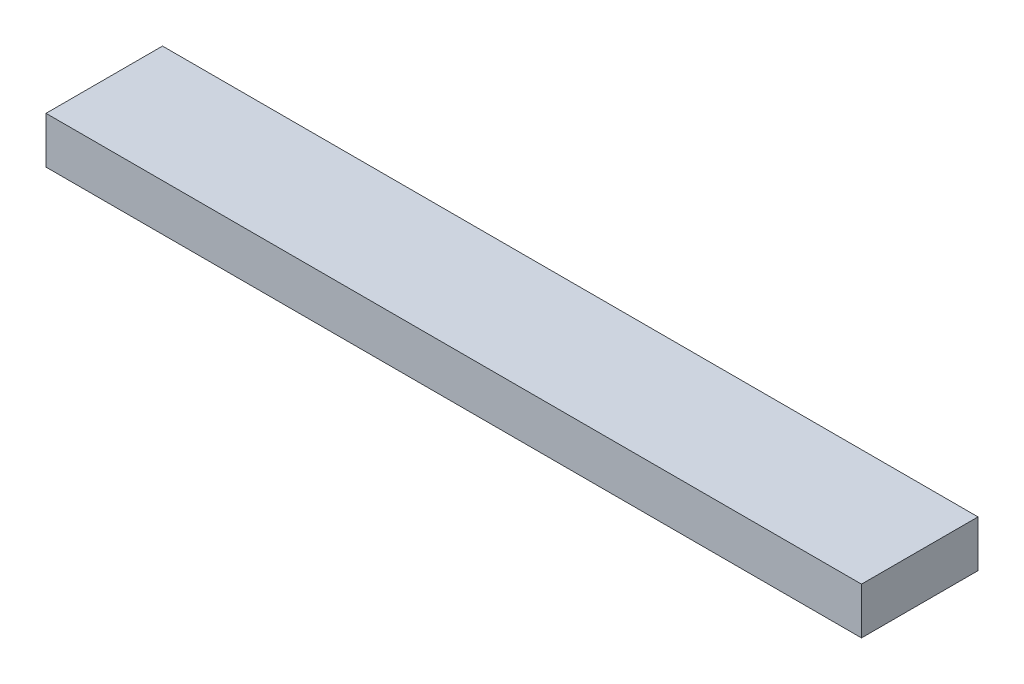
SolidWorks part; units mm, degrees
ref_plane "Front Plane" through (0, 0, 0) normal (0, 0, 1) x (1, 0, 0)
ref_plane "Top Plane" through (0, 0, 0) normal (0, 1, 0) x (1, 0, 0)
ref_plane "Right Plane" through (0, 0, 0) normal (1, 0, 0) x (0, 0, -1)
sketch "Sketch1" plane through (0, 0, 0) normal (0, 1, 0) x (1, 0, 0)
  line L1 (-175, 25) -> (175, 25)
  line L2 (-175, 25) -> (-175, -25)
  line L3 (-175, -25) -> (175, -25)
  line L4 (175, 25) -> (175, -25)
  line L5 (-175, 25) -> (175, -25) construction
  line L6 (-175, -25) -> (175, 25) construction
  point P0 (0, 0)
  dimension "D1" = 350
  dimension "D2" = 50
extrude "Boss-Extrude1" add sketch "Sketch1" along normal mid plane 20
